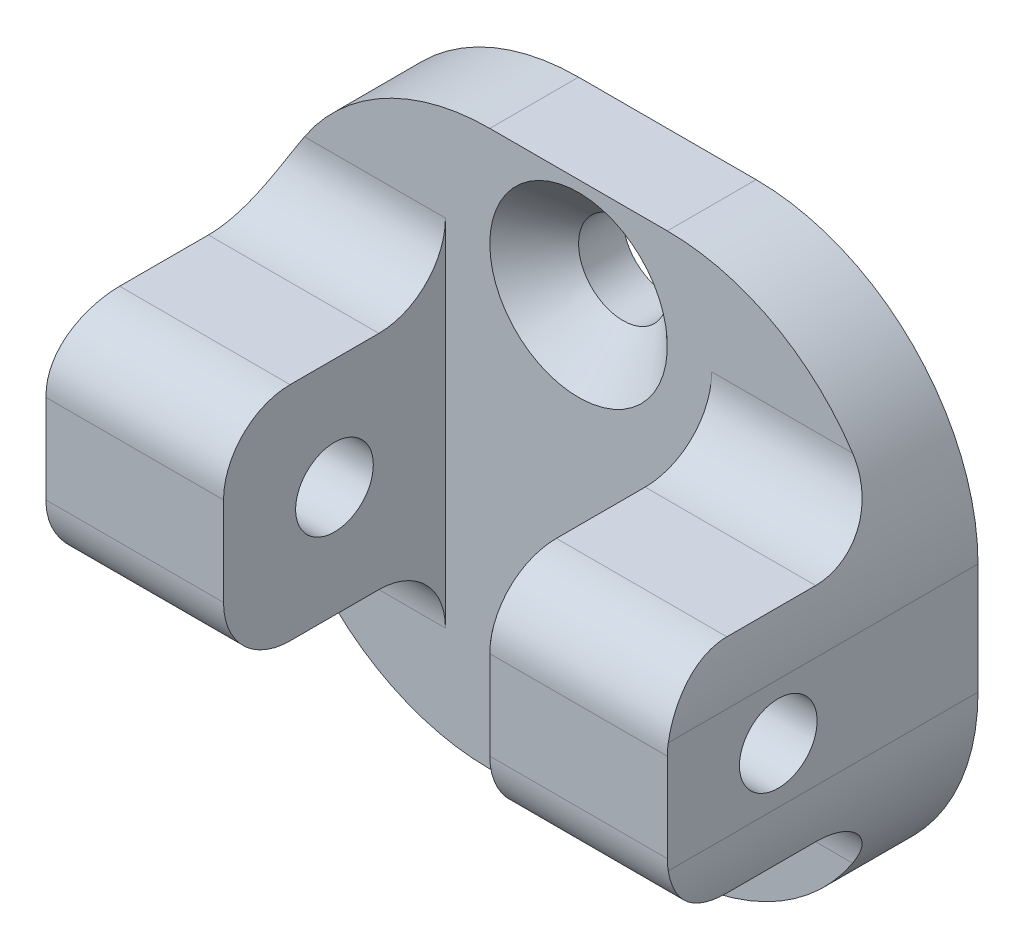
SolidWorks part; units mm, degrees
ref_plane "Plan de face" through (0, 0, 0) normal (0, 0, 1) x (1, 0, 0)
ref_plane "Plan de dessus" through (0, 0, 0) normal (0, 1, 0) x (1, 0, 0)
ref_plane "Plan de droite" through (0, 0, 0) normal (1, 0, 0) x (0, 0, -1)
sketch "Esquisse1" plane through (0, 0, 0) normal (0, 0, 1) x (1, 0, 0)
  line L1 (0, 0) -> (28, 0)
  line L2 (0, 0) -> (0, 25)
  line L3 (0, 25) -> (28, 25)
  line L4 (28, 0) -> (28, 25)
  dimension "D1" = 25
  dimension "D2" = 28
extrude "Boss.-Extru.1" add sketch "Esquisse1" along normal blind 4
sketch "Esquisse2" plane through (0, 0, 4) normal (0, 0, 1) x (1, 0, 0)
  line L0 (0, 12.5) -> (28, 12.5) construction
  line L1 (0, 25) -> (0, 0) construction
  line L2 (28, 0) -> (28, 25) construction
  line L4 (0, 17.5) -> (28, 17.5)
  line L5 (0, 17.5) -> (0, 7.5)
  line L6 (0, 7.5) -> (28, 7.5)
  line L7 (28, 17.5) -> (28, 7.5)
  line L8 (0, 17.5) -> (28, 7.5) construction
  line L9 (0, 7.5) -> (28, 17.5) construction
  point P6 (14, 12.5)
  dimension "D1" = 10
extrude "Boss.-Extru.2" add sketch "Esquisse2" along normal blind 10
sketch "Esquisse3" plane through (28, 0, 0) normal (1, 0, 0) x (0, 0, -1)
  line L0 (-14, 12.5) -> (-9, 12.5) construction
  line L1 (-14, 7.5) -> (-14, 17.5) construction
  circle A0 centre (-9, 12.5) radius 1.75
  dimension "D1" = 3.5
  dimension "D2" = 5
extrude "Enlèv. mat.-Extru.1" cut sketch "Esquisse3" against normal through all both and the other way through all
fillet "Congé1" radius 3 4 edges at (14, 7.5, 14) (14, 7.5, 4) (14, 17.5, 4) (14, 17.5, 14)
sketch "Esquisse4" plane through (0, 0, 4) normal (0, 0, 1) x (1, 0, 0)
  line L0 (0, 12.5) -> (28, 12.5) construction
  line L1 (28, 14.5) -> (28, 17.5) construction
  line L3 (0, 14.5) -> (0, 10.5) construction
  line L4 (8, 20.5) -> (20, 20.5)
  line L5 (8, 20.5) -> (8, 4.5)
  line L6 (8, 4.5) -> (20, 4.5)
  line L7 (20, 20.5) -> (20, 4.5)
  line L8 (8, 20.5) -> (20, 4.5) construction
  line L9 (8, 4.5) -> (20, 20.5) construction
  line L10 (28, 4.5) -> (0, 4.5) construction
  point P7 (14, 12.5)
  dimension "D1" = 12
extrude "Enlèv. mat.-Extru.2" cut sketch "Esquisse4" along normal blind 10
sketch "Esquisse5" plane through (0, 0, 4) normal (0, 0, 1) x (1, 0, 0)
  line L0 (14, 0) -> (14, 25) construction
  line L1 (0, 0) -> (28, 0) construction
  line L2 (28, 25) -> (0, 25) construction
  line L3 (14, 12.5) -> (0, 12.5) construction
  line L4 (0, 14.5) -> (0, 10.5) construction
  circle A0 centre (14, 20.5) radius 2
  circle A1 centre (14, 4.5) radius 2
  dimension "D1" = 16
  dimension "D2" = 4
extrude "Enlèv. mat.-Extru.3" cut sketch "Esquisse5" against normal through all both and the other way through all
chamfer "Chanfrein1" distance 2 angle 45 2 edges at (12, 20.5, 4) (12, 4.5, 4)
fillet "Congé2" radius 10 4 edges at (28, 0, 2) (0, 0, 2) (0, 25, 2) (28, 25, 2)
